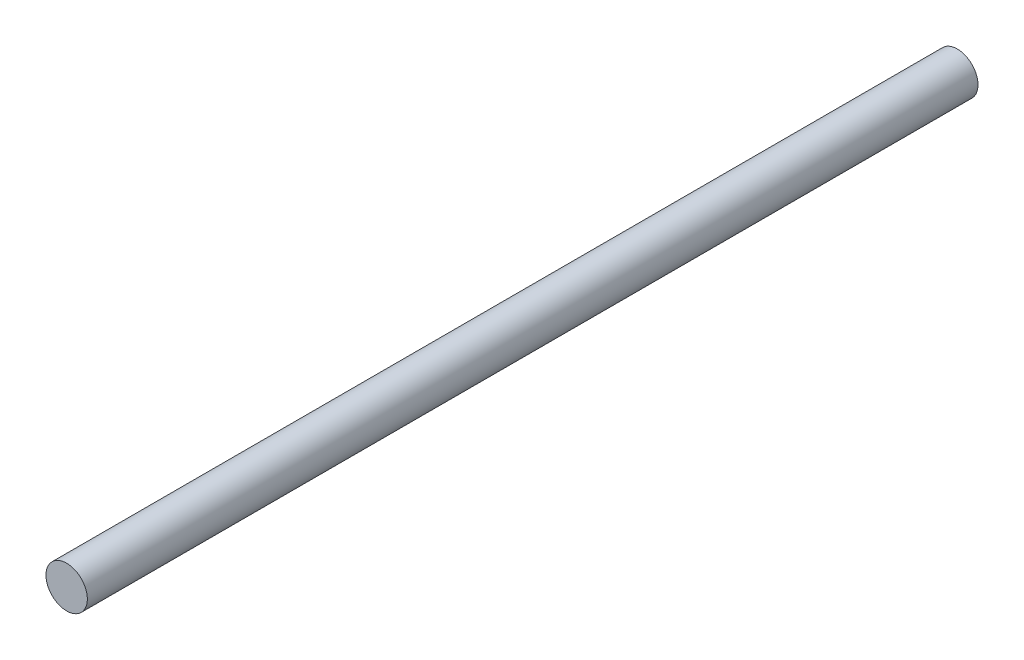
SolidWorks part; units mm, degrees
material "Hierro dúctil"
ref_plane "Alzado" through (0, 0, 0) normal (0, 0, 1) x (1, 0, 0)
ref_plane "Planta" through (0, 0, 0) normal (0, 1, 0) x (1, 0, 0)
ref_plane "Vista lateral" through (0, 0, 0) normal (1, 0, 0) x (0, 0, -1)
sketch "Croquis2" plane through (0, 0, 0) normal (0, 0, 1) x (1, 0, 0)
  circle A0 centre (0, 44.6491) radius 3.025
extrude "Saliente-Extruir1" add sketch "Croquis2" along normal mid plane 140 from offset 0
sketch "Croquis3" plane through (0, 0, 70) normal (0, 0, 1) x (1, 0, 0)
  circle A0 centre (0, 44.6491) radius 3.025
sketch "Croquis4" plane through (0, 0, 0) normal (1, 0, 0) x (0, 0, -1)
  line L1 (60.2, 47.6914) -> (91.3262, 47.6914)
  line L2 (60.2, 47.6914) -> (60.2, 40.3584)
  line L3 (60.2, 40.3584) -> (91.3262, 40.3584)
  line L4 (91.3262, 47.6914) -> (91.3262, 40.3584)
extrude "Cortar-Extruir1" cut sketch "Croquis4" against normal mid plane 20
